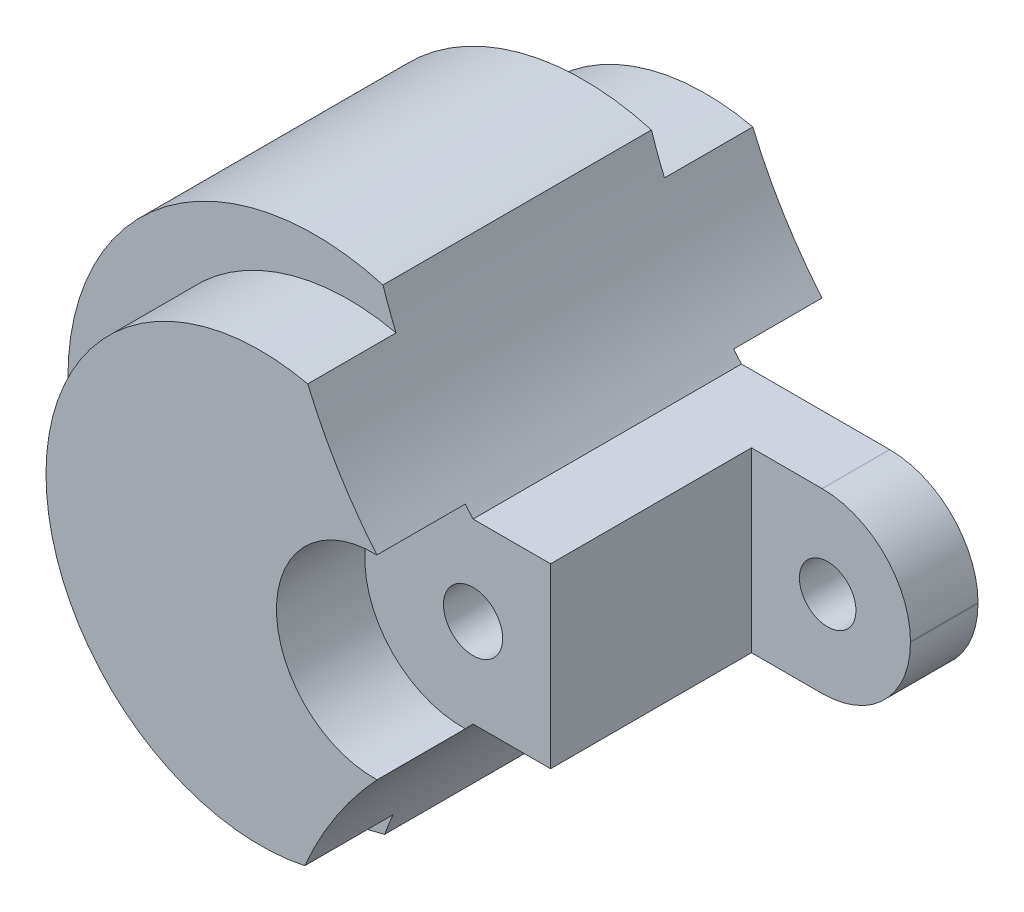
SolidWorks part; units mm, degrees
ref_plane "前视基准面" through (0, 0, 0) normal (0, 0, 1) x (1, 0, 0)
ref_plane "上视基准面" through (0, 0, 0) normal (0, 1, 0) x (1, 0, 0)
ref_plane "右视基准面" through (0, 0, 0) normal (1, 0, 0) x (0, 0, -1)
sketch "草图1" plane through (0, 0, 0) normal (0, 0, 1) x (1, 0, 0)
  line L0 (1.5398, 12.851) -> (15.553, 14.251)
  line L1 (-16.647, 18.901) -> (15.553, 18.901) construction
  line L2 (-16.647, 18.901) -> (-16.647, 12.851) construction
  line L3 (-16.647, 12.851) -> (15.553, 12.851) construction
  line L4 (15.553, 18.901) -> (15.553, 12.851) construction
  line L5 (-16.647, 18.901) -> (15.553, 12.851) construction
  line L6 (-16.647, 12.851) -> (15.553, 18.901) construction
  line L7 (14.1183, 17.876) -> (16.9877, 17.876) construction
  line L8 (14.1183, 17.876) -> (14.1183, 13.876) construction
  line L9 (14.1183, 13.876) -> (16.9877, 13.876) construction
  line L10 (16.9877, 17.876) -> (16.9877, 13.876) construction
  line L11 (14.1183, 17.876) -> (16.9877, 13.876) construction
  line L12 (14.1183, 13.876) -> (16.9877, 17.876) construction
  line L13 (15.553, 17.876) -> (1.5005, 18.901)
  line L14 (-0.547, 19.551) -> (-0.547, 12.201) construction
  line L15 (-0.547, 19.551) -> (-0.547, 20.901)
  line L16 (-0.547, 20.901) -> (19.5128, 20.901)
  line L17 (19.5128, 20.901) -> (41.453, 20.901)
  line L18 (-0.547, 12.201) -> (-0.547, 10.851)
  line L19 (-0.547, 10.851) -> (41.453, 10.851)
  line L20 (41.453, 20.901) -> (41.453, 10.851)
  line L21 (-0.547, 15.876) -> (3.9081, 15.876) construction
  circle A0 centre (-0.547, 15.876) radius 3.675 construction
  arc A1 (15.553, 14.251) -> (15.553, 17.876) centre (15.3719, 16.0635) ccw
  arc A2 (1.5398, 12.851) -> (-0.547, 12.201) centre (-0.547, 15.876) cw
  arc A3 (1.5005, 18.901) -> (-0.547, 19.551) centre (-0.547, 16.001) ccw
  point P6 (15.553, 15.876)
  dimension "D1" = 7.35
  dimension "D2" = 16.1
  dimension "D3" = 6.05
  dimension "D4" = 4
  dimension "D5" = 2
  dimension "D6" = 2
  dimension "D7" = 42
  dimension "D8" = 10.05
extrude "凸台-拉伸1" add sketch "草图1" along normal blind 2.2
sketch "草图2" plane through (0, 0, 0) normal (0, 0, -1) x (-1, 0, 0)
  line L0 (-19.5128, 10.851) -> (-49.453, 10.851)
  line L1 (-19.5128, 20.901) -> (0.547, 20.901)
  line L2 (-49.453, 10.851) -> (-49.453, 20.901)
  line L3 (-19.5128, 10.851) -> (0.547, 10.851)
  line L4 (0.547, 20.901) -> (0.547, 10.851)
  line L5 (-49.453, 20.901) -> (-19.5128, 20.901)
extrude "凸台-拉伸2" add sketch "草图2" along normal blind 3.25
sketch "草图3" plane through (0, 0, 2.2) normal (0, 0, 1) x (1, 0, 0)
  line L1 (-0.547, 20.901) -> (49.453, 20.901)
  line L3 (-0.547, 20.901) -> (-0.547, 10.851)
  line L4 (-0.547, 10.851) -> (49.453, 10.851)
  line L5 (49.453, 20.901) -> (49.453, 10.851)
extrude "凸台-拉伸3" add sketch "草图3" along normal blind 3.25
sketch "草图4" plane through (0, 0, 0) normal (0, 0, 1) x (1, 0, 0)
  line L0 (1.5005, 18.901) -> (1.5398, 12.851) construction
  line L1 (-0.547, 20.901) -> (-0.547, 10.851) construction
  line L2 (-0.547, 19.551) -> (-2.2354, 16.6161)
  line L3 (-2.2354, 16.6161) -> (-1.1109, 12.3105)
  line L4 (-1.1109, 12.3105) -> (-0.547, 12.201)
  arc A0 (1.5398, 12.851) -> (-0.547, 12.201) centre (-0.547, 15.876) cw
  arc A1 (-0.547, 19.551) -> (1.5398, 12.851) centre (-0.547, 15.876) ccw construction
  arc A2 (1.5005, 18.901) -> (-0.547, 19.551) centre (-0.547, 16.001) ccw
  arc A3 (1.5005, 18.901) -> (-0.547, 19.551) centre (-0.547, 16.001) ccw construction
  arc A4 (1.5005, 18.901) -> (1.5398, 12.851) centre (-1.5048, 15.8564) cw
extrude "切除-拉伸1" cut sketch "草图4" against normal mid plane 60
sketch "草图6" plane through (0, 0, -3.25) normal (0, 0, -1) x (-1, 0, 0)
  line L0 (-49.453, 15.876) -> (-51.7312, 15.876) construction
  line L2 (-49.453, 20.901) -> (-49.453, 10.851) construction
  circle A0 centre (-49.453, 15.876) radius 5.025
extrude "凸台-拉伸4" add sketch "草图6" against normal up to surface (8.7 mm away) up to face at (12.6389, 15.877, 5.45)
sketch "草图7" plane through (41.453, 0, 0) normal (1, 0, 0) x (0, 0, -1)
  line L0 (-1.1, 20.901) -> (-1.1, 19.7727) construction
  line L3 (-2.6, 22.1945) -> (0.4, 22.1945)
  line L4 (-2.6, 22.1945) -> (-2.6, 10.0543)
  line L5 (-2.6, 10.0543) -> (0.4, 10.0543)
  line L6 (0.4, 22.1945) -> (0.4, 10.0543)
  line L7 (-2.6, 22.1945) -> (0.4, 10.0543) construction
  line L8 (-2.6, 10.0543) -> (0.4, 22.1945) construction
  point P1 (-1.1, 16.1244)
  dimension "D1" = 3
sketch "草图8" plane through (0, 0, -3.25) normal (0, 0, -1) x (-1, 0, 0)
  line L0 (0.547, 19.551) -> (0.547, 20.901) construction
  circle A0 centre (-49.453, 15.876) radius 1.675
  circle A1 centre (-7.953, 15.8564) radius 0.84
  dimension "D1" = 3.35
  dimension "D2" = 1.68
  dimension "D3" = 8.5
extrude "切除-拉伸3" cut sketch "草图8" against normal blind 55
sketch "草图9" plane through (0, 0, -3.25) normal (0, 0, -1) x (-1, 0, 0)
  line L1 (-28.4121, 22.3056) -> (-56.8851, 22.3056)
  line L2 (-28.4121, 22.3056) -> (-28.4121, 7.7732)
  line L3 (-28.4121, 7.7732) -> (-56.8851, 7.7732)
  line L4 (-56.8851, 22.3056) -> (-56.8851, 7.7732)
extrude "切除-拉伸4" cut sketch "草图9" against normal blind 3
sketch "草图10" plane through (0, 0, 2.2) normal (0, 0, -1) x (-1, 0, 0)
  line L0 (-49.453, 20.901) -> (-38.4664, 20.901)
  line L1 (-49.453, 20.901) -> (-28.4121, 20.901) construction
  line L2 (-38.4664, 20.901) -> (-38.4664, 10.851)
  line L3 (-28.4121, 10.851) -> (-49.453, 10.851) construction
  line L4 (-38.4664, 10.851) -> (-49.453, 10.851)
  arc A0 (-49.453, 10.851) -> (-49.453, 20.901) centre (-51.7381, 15.876) ccw
extrude "凸台-拉伸5" add sketch "草图10" along normal up to surface (2.45 mm away) up to face at (51.128, 15.876, -0.25)
sketch "草图11" plane through (0, 0, -3.25) normal (0, 0, -1) x (-1, 0, 0)
  line L0 (-49.453, 20.901) -> (-28.4121, 20.901) construction
  line L1 (-38.9326, 20.901) -> (-26.3184, 20.901)
  line L2 (-38.9326, 20.901) -> (-38.9326, 10.851)
  line L3 (-38.9326, 10.851) -> (-26.3184, 10.851)
  line L4 (-26.3184, 20.901) -> (-26.3184, 10.851)
  line L5 (-28.4121, 10.851) -> (0.547, 10.851) construction
extrude "凸台-拉伸6" add sketch "草图11" against normal up to surface (3 mm away) up to face at (40.1888, 15.876, -0.25)
sketch "草图12" plane through (0, 0, -3.25) normal (0, 0, -1) x (-1, 0, 0)
  line L0 (-38.9326, 20.901) -> (-38.9326, 10.851) construction
  line L1 (-23.9326, 22.7776) -> (12.6959, 22.7776)
  line L2 (-23.9326, 22.7776) -> (-23.9326, 7.4291)
  line L3 (-23.9326, 7.4291) -> (12.6959, 7.4291)
  line L4 (12.6959, 22.7776) -> (12.6959, 7.4291)
  point P6 (-38.9326, 15.876)
  dimension "D1" = 15
extrude "切除-拉伸5" cut sketch "草图12" against normal blind 10 contours L4 L3 L2 L1
sketch "草图13" plane through (23.9326, 0, 0) normal (-1, 0, 0) x (0, 0, 1)
  line L1 (-1.575, 18.7994) -> (3.775, 18.7994)
  line L2 (-1.575, 18.7994) -> (-1.575, 13.4494)
  line L3 (-1.575, 13.4494) -> (3.775, 13.4494)
  line L4 (3.775, 18.7994) -> (3.775, 13.4494)
  line L5 (-1.575, 18.7994) -> (3.775, 13.4494) construction
  line L6 (-1.575, 13.4494) -> (3.775, 18.7994) construction
  point P0 (1.1, 16.1244)
  dimension "D1" = 5.35
  dimension "D2" = 5.35
extrude "切除-拉伸6" cut sketch "草图13" against normal blind 14
sketch "草图14" plane through (0, 20.901, 0) normal (0, 1, 0) x (1, 0, 0)
  circle A0 centre (30.5382, -1.1) radius 1.1
  dimension "D1" = 2.2
extrude "切除-拉伸7" cut sketch "草图14" against normal blind 14
sketch "草图15" plane through (0, 0, 5.45) normal (0, 0, 1) x (1, 0, 0)
  circle A0 centre (36.8799, 15.8828) radius 1.1
extrude "切除-拉伸8" cut sketch "草图15" against normal blind 10
sketch "草图16" plane through (0, 0, -0.25) normal (0, 0, -1) x (-1, 0, 0)
  line L1 (-49.453, 20.901) -> (23.547, 20.901)
  line L2 (-49.453, 20.901) -> (-49.453, 10.851)
  line L3 (-49.453, 10.851) -> (23.547, 10.851)
  circle A0 centre (23.547, 15.876) radius 5.025 construction
  arc A1 (23.547, 20.901) -> (23.547, 10.851) centre (23.547, 15.876) cw
  circle A2 centre (23.547, 15.876) radius 1.625
  dimension "D2" = 3.25
  dimension "D1" = 73
extrude "凸台-拉伸7" add sketch "草图16" against normal up to surface (5.7 mm away) up to face at (37.9799, 15.8828, 5.45)
sketch "草图17" plane through (0, 0, -3.25) normal (0, 0, -1) x (-1, 0, 0)
  line L1 (-43.1398, 23.5488) -> (-23.2167, 23.5488)
  line L2 (-43.1398, 23.5488) -> (-43.1398, 8.4657)
  line L3 (-43.1398, 8.4657) -> (-23.2167, 8.4657)
  line L4 (-23.2167, 23.5488) -> (-23.2167, 8.4657)
extrude "切除-拉伸9" cut sketch "草图17" against normal up to surface (3 mm away) up to face at (-25.172, 15.876, -0.25)
sketch "草图18" plane through (0, 0, -0.25) normal (0, 0, -1) x (-1, 0, 0)
  line L0 (-49.453, 17.551) -> (-49.453, 14.201) construction
  line L1 (-31.6616, 15.876) -> (8.461, 15.876) construction
  line L2 (-31.6616, 17.3033) -> (8.461, 17.3033)
  line L3 (-31.6616, 14.4488) -> (8.461, 14.4488)
  circle A0 centre (-49.453, 15.876) radius 1.675
  arc A1 (-31.6616, 17.3033) -> (-31.6616, 14.4488) centre (-31.6616, 15.876) ccw
  arc A2 (8.461, 14.4488) -> (8.461, 17.3033) centre (8.461, 15.876) ccw
  circle A3 centre (14.8432, 15.876) radius 1.6
  point P6 (-11.6003, 15.876)
  dimension "D1" = 3.2
extrude "切除-拉伸10" cut sketch "草图18" against normal blind 6
sketch "草图19" plane through (0, 0, -0.25) normal (0, 0, -1) x (-1, 0, 0)
  line L0 (-49.453, 20.901) -> (23.547, 20.901) construction
  line L1 (23.547, 10.851) -> (-49.453, 10.851) construction
  line L2 (12.6975, 20.901) -> (-60.9995, 39.3751)
  line L3 (-60.9995, 39.3751) -> (-58.7388, -10.2285)
  line L4 (-58.7388, -10.2285) -> (12.6975, 10.851)
  line L5 (12.6975, 20.901) -> (10.1565, 20.901)
  line L6 (10.1565, 20.901) -> (10.1565, 10.851)
  line L7 (10.1565, 10.851) -> (12.6975, 10.851)
extrude "切除-拉伸11" cut sketch "草图19" against normal blind 10
sketch "草图21" plane through (0, 0, 5.45) normal (0, 0, 1) x (1, 0, 0)
  line L0 (-23.547, 10.851) -> (-10.1565, 10.851) construction
  line L1 (-23.547, 20.901) -> (-12.6975, 20.901)
  line L2 (-12.6975, 10.851) -> (-23.547, 10.851)
  arc A0 (-23.547, 20.901) -> (-23.547, 10.851) centre (-23.547, 15.876) ccw
  arc A1 (-23.547, 20.901) -> (-23.547, 10.851) centre (-23.547, 15.876) ccw construction
  arc A2 (-12.6975, 20.901) -> (-12.6975, 10.851) centre (-15.7692, 15.876) cw
  arc A3 (-12.6975, 10.851) -> (-9.8814, 15.736) centre (-15.7692, 15.876) ccw construction
extrude "凸台-拉伸8" add sketch "草图21" along normal blind 9.5
sketch "草图22" plane through (0, 0, -0.25) normal (0, 0, -1) x (-1, 0, 0)
  line L0 (23.547, 20.901) -> (26.6011, 16.3683)
  line L1 (26.6011, 16.3683) -> (23.547, 10.851)
  arc A1 (23.547, 20.901) -> (28.6467, 29.831) centre (4.5206, 37.6876) ccw
  arc A2 (23.547, 10.851) -> (23.547, 20.901) centre (23.547, 15.876) ccw construction
  arc A3 (23.547, 10.851) -> (28.5553, 2.9319) centre (8.008, -4.5196) cw
  arc A4 (28.6467, 29.831) -> (28.5553, 2.9319) centre (32.4879, 16.3683) cw
  point P0 (32.4879, 16.3683)
  dimension "D2" = 14
extrude "凸台-拉伸9" add sketch "草图22" against normal up to surface (15.2 mm away) up to face at (-18.6741, 15.876, 14.95)
sketch "草图23" plane through (-10.1565, 0, 0) normal (1, 0, 0) x (0, 0, -1)
  line L1 (-18.3686, 21.4962) -> (-3.5748, 21.4962)
  line L2 (-18.3686, 21.4962) -> (-18.3686, 9.899)
  line L3 (-18.3686, 9.899) -> (-3.5748, 9.899)
  line L4 (-3.5748, 21.4962) -> (-3.5748, 9.899)
  line L5 (-18.3686, 21.4962) -> (-3.5748, 9.899) construction
  line L6 (-18.3686, 9.899) -> (-3.5748, 21.4962) construction
  point P0 (-10.9717, 15.6976)
extrude "切除-拉伸12" cut sketch "草图23" against normal mid plane 18
sketch "草图25" plane through (0, 0, -0.25) normal (0, 0, -1) x (-1, 0, 0)
  circle A0 centre (14.8432, 15.876) radius 1.6
  circle A1 centre (23.547, 15.876) radius 1.674
extrude "切除-拉伸13" cut sketch "草图25" against normal blind 20
fillet "圆角1" radius 5 2 edges at (-10.1565, 20.901, 1.6624) (-10.1565, 10.851, 1.6624)
sketch "草图26" plane through (0, 0, -0.25) normal (0, 0, -1) x (-1, 0, 0)
  arc A0 (23.9895, 21.4162) -> (23.9823, 10.3981) centre (24.1658, 15.9071) cw
  arc A1 (23.547, 20.901) -> (28.6467, 29.831) centre (4.5206, 37.6876) ccw construction
  arc A2 (28.5553, 2.9319) -> (23.547, 10.851) centre (8.008, -4.5196) ccw construction
  arc A3 (23.9895, 21.4162) -> (27.9082, 27.8481) centre (4.5206, 37.6876) ccw
  arc A5 (23.547, 20.901) -> (28.6467, 29.831) centre (4.5206, 37.6876) ccw construction
  arc A6 (23.9823, 10.3981) -> (28.0789, 4.1335) centre (8.008, -4.5196) cw
  arc A7 (28.5553, 2.9319) -> (23.547, 10.851) centre (8.008, -4.5196) ccw construction
  arc A8 (28.0789, 4.1335) -> (27.9082, 27.8481) centre (30.5897, 16.0095) ccw
  point P21 (27.7622, 4.8341)
  point P22 (27.9082, 27.8481)
extrude "凸台-拉伸10" add sketch "草图26" along normal blind 5
sketch "草图27" plane through (0, 0, -5.25) normal (0, 0, -1) x (-1, 0, 0)
  arc A0 (23.9895, 21.4162) -> (23.9823, 10.3981) centre (24.1658, 15.9071) cw
  arc A1 (27.9082, 27.8481) -> (23.9895, 21.4162) centre (4.5206, 37.6876) cw
  arc A2 (23.9823, 10.3981) -> (28.0789, 4.1335) centre (8.008, -4.5196) cw
  arc A3 (28.0789, 4.1335) -> (27.9082, 27.8481) centre (30.5897, 16.0095) ccw
extrude "凸台-拉伸11" add sketch "草图27" against normal blind 25.2
sketch "草图28" plane through (0, 0, 19.95) normal (0, 0, 1) x (1, 0, 0)
  line L0 (-53.7117, 22.8654) -> (-36.6552, -4.8534)
  line L1 (-36.6552, -4.8534) -> (-37.2374, -5.2117)
  line L2 (-37.2374, -5.2117) -> (-54.3062, 22.5272)
  line L3 (-54.3062, 22.5272) -> (-53.7117, 22.8654)
